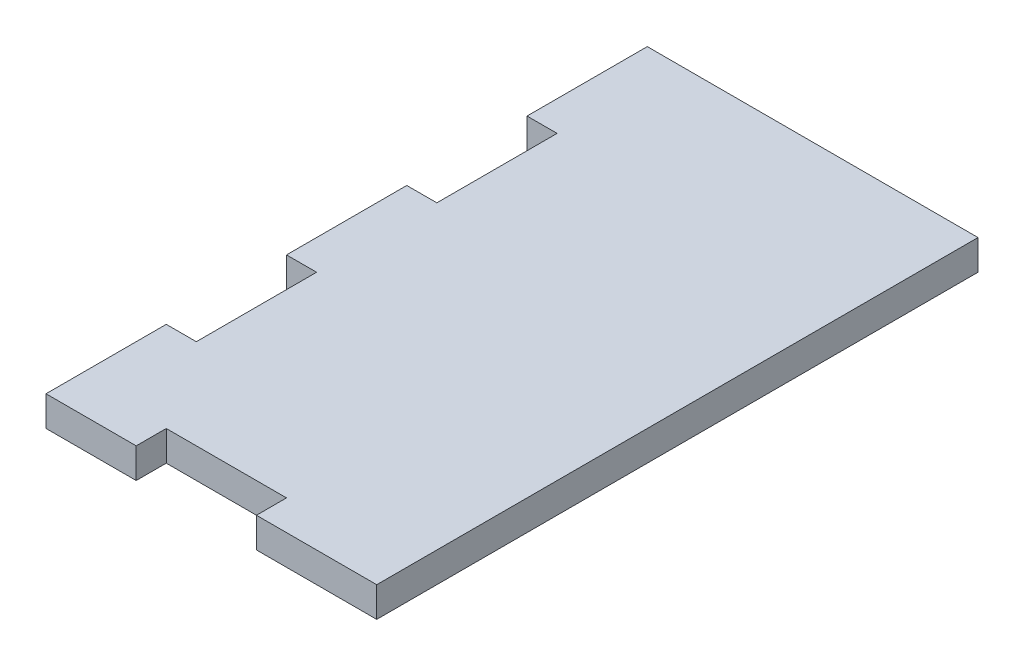
SolidWorks part; units mm, degrees
ref_plane "Front Plane" through (0, 0, 0) normal (0, 0, 1) x (1, 0, 0)
ref_plane "Top Plane" through (0, 0, 0) normal (0, 1, 0) x (1, 0, 0)
ref_plane "Right Plane" through (0, 0, 0) normal (1, 0, 0) x (0, 0, -1)
sketch "Sketch2" plane through (0, 0, 0) normal (0, 1, 0) x (1, 0, 0)
  line L0 (31.75, 3.175) -> (31.75, 63.5)
  line L1 (0, 0) -> (31.75, 0)
  line L2 (0, 0) -> (0, 63.5)
  line L3 (0, 63.5) -> (31.75, 63.5)
  line L5 (0, 0) -> (-3.175, 0)
  line L6 (0, 0) -> (0, 12.7)
  line L7 (0, 12.7) -> (-3.175, 12.7)
  line L8 (-3.175, 0) -> (-3.175, 12.7)
  line L9 (0, 25.4) -> (-3.175, 25.4)
  line L10 (0, 25.4) -> (0, 38.1)
  line L11 (0, 38.1) -> (-3.175, 38.1)
  line L12 (-3.175, 25.4) -> (-3.175, 38.1)
  line L13 (0, 50.8) -> (-3.175, 50.8)
  line L14 (0, 50.8) -> (0, 63.5)
  line L15 (0, 63.5) -> (-3.175, 63.5)
  line L16 (-3.175, 50.8) -> (-3.175, 63.5)
  line L17 (6.35, 0) -> (19.05, 0)
  line L18 (6.35, 0) -> (6.35, 3.175)
  line L19 (6.35, 3.175) -> (19.05, 3.175)
  line L20 (19.05, 0) -> (19.05, 3.175)
  line L22 (31.75, 0) -> (31.75, 3.175)
  dimension "D1" = 3.175
  dimension "D2" = 12.7
  dimension "D3" = 12.7
  dimension "D4" = 3.175
  dimension "D5" = 12.7
  dimension "D7" = 12.7
  dimension "D8" = 3.175
  dimension "D9" = 12.7
  dimension "D10" = 3.175
  dimension "D11" = 12.7
  dimension "D13" = 3.175
  dimension "D14" = 6.35
  dimension "D15" = 12.7
extrude "Boss-Extrude2" add sketch "Sketch2" along normal blind 3.175
